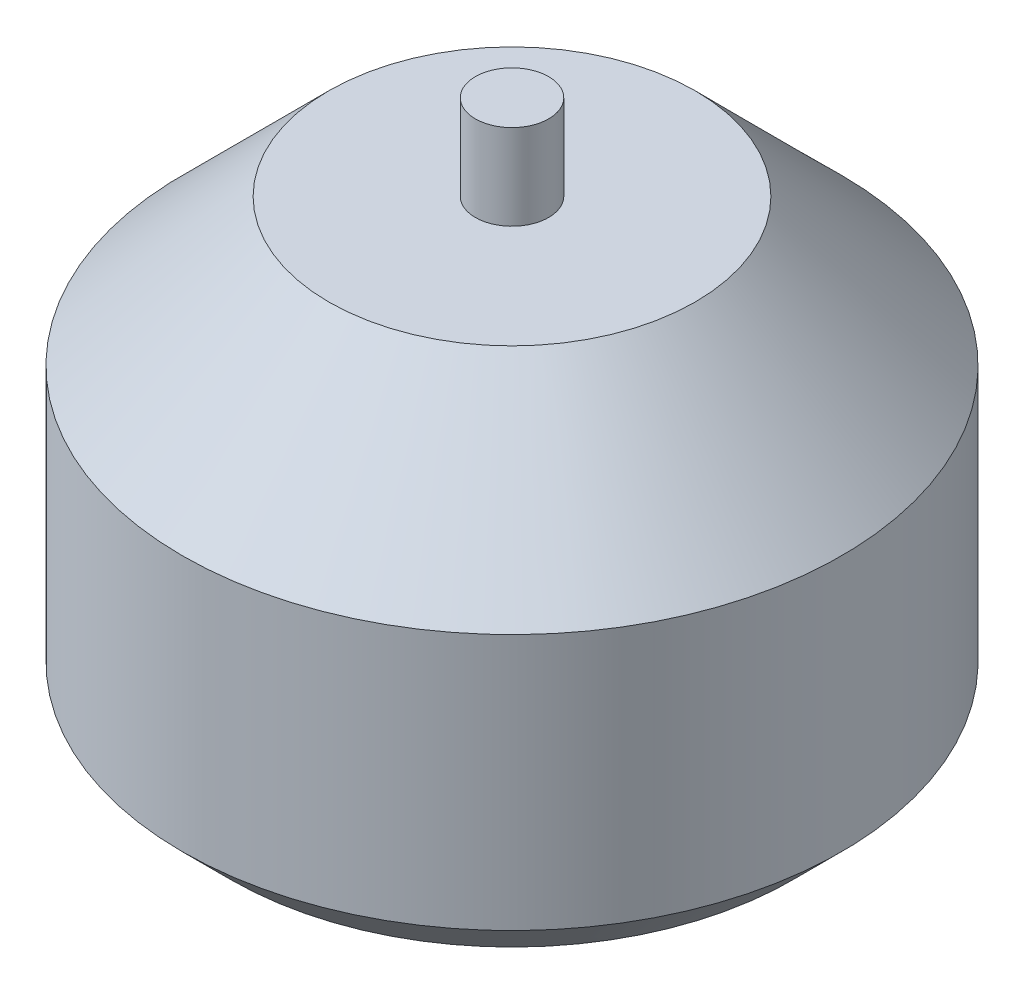
SolidWorks part; units mm, degrees
ref_plane "Front Plane" through (0, 0, 0) normal (0, 0, 1) x (1, 0, 0)
ref_plane "Top Plane" through (0, 0, 0) normal (0, 1, 0) x (1, 0, 0)
ref_plane "Right Plane" through (0, 0, 0) normal (1, 0, 0) x (0, 0, -1)
sketch "Sketch1" plane through (0, 0, 0) normal (0, 1, 0) x (1, 0, 0)
  circle A0 centre (0, 0) radius 13.5
  dimension "D1" = 27
extrude "Boss-Extrude1" add sketch "Sketch1" along normal blind 18.5
sketch "Sketch2" plane through (0, 18.5, 0) normal (0, 1, 0) x (1, 0, 0)
  circle A0 centre (0, 0) radius 1.5
  dimension "D1" = 3
extrude "Boss-Extrude2" add sketch "Sketch2" along normal blind 3.5
sketch "Sketch3" plane through (0, 0, 0) normal (0, -1, 0) x (1, 0, 0)
  circle A0 centre (0, 0) radius 1.5
  dimension "D1" = 3
extrude "Boss-Extrude3" add sketch "Sketch3" along normal blind 3
chamfer "Chamfer1" distance 6 angle 45 1 edges at (0, 18.5, 13.5)
chamfer "Chamfer2" distance 2 angle 45 1 edges at (0, 0, 13.5)
